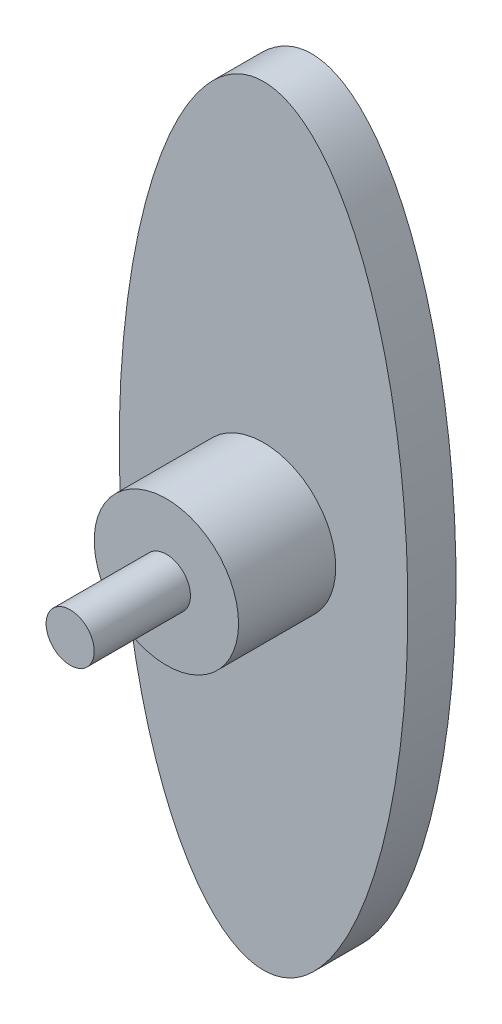
SolidWorks part; units mm, degrees
ref_plane "Front Plane" through (0, 0, 0) normal (0, 0, 1) x (1, 0, 0)
ref_plane "Top Plane" through (0, 0, 0) normal (0, 1, 0) x (1, 0, 0)
ref_plane "Right Plane" through (0, 0, 0) normal (1, 0, 0) x (0, 0, -1)
sketch "Sketch1" plane through (0, 0, 0) normal (0, 0, 1) x (1, 0, 0)
  ellipse E0 centre (0, 0) end of major axis (0, -50.8) minor radius 19.05
  point P1 (0, -50.8)
  point P7 (0, 0)
  point P9 (0, 0)
  point P10 (0, 0)
  dimension "D1" = 50.8
  dimension "D2" = 19.05
extrude "Boss-Extrude1" add sketch "Sketch1" along normal mid plane 6.35
sketch "Sketch2" plane through (0, 0, 0) normal (0, 0, 1) x (1, 0, 0)
  circle A0 centre (0, 0) radius 9.525
  dimension "D1" = 19.05
extrude "Boss-Extrude2" add sketch "Sketch2" along normal blind 16.002
sketch "Sketch3" plane through (0, 0, 0) normal (0, 0, 1) x (1, 0, 0)
  circle A0 centre (0, 0) radius 3.175
  dimension "D1" = 6.35
extrude "Boss-Extrude3" add sketch "Sketch3" along normal blind 28.702
